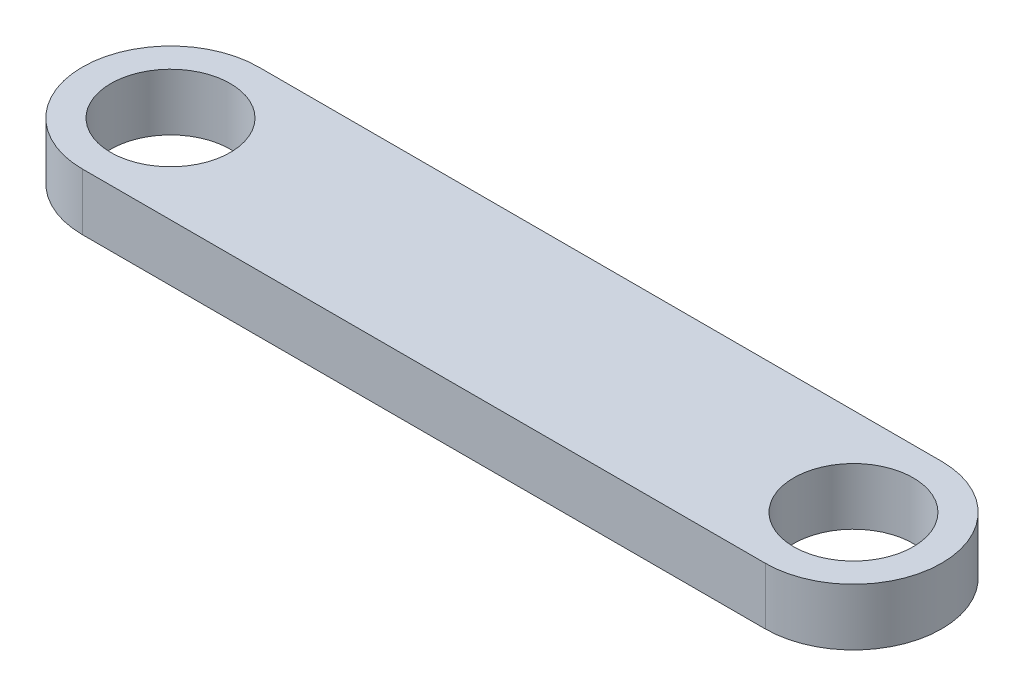
SolidWorks part; units mm, degrees
ref_plane "Front Plane" through (0, 0, 0) normal (0, 0, 1) x (1, 0, 0)
ref_plane "Top Plane" through (0, 0, 0) normal (0, 1, 0) x (1, 0, 0)
ref_plane "Right Plane" through (0, 0, 0) normal (1, 0, 0) x (0, 0, -1)
sketch "Sketch1" plane through (0, 0, 0) normal (0, 1, 0) x (1, 0, 0)
  line L0 (0, 0) -> (30.48, 0) construction
  line L1 (0, 3.937) -> (30.48, 3.937)
  line L2 (0, -3.937) -> (30.48, -3.937)
  arc A0 (0, 3.937) -> (0, -3.937) centre (0, 0) ccw
  arc A1 (30.48, -3.937) -> (30.48, 3.937) centre (30.48, 0) ccw
  circle A2 centre (0, 0) radius 2.667
  circle A3 centre (30.48, 0) radius 2.667
  point P3 (15.24, 0)
  dimension "D1" = 5.334
  dimension "D2" = 5.334
  dimension "D3" = 30.48
  dimension "D4" = 7.874
extrude "Boss-Extrude1" add sketch "Sketch1" along normal blind 2.54
equation "\"press fit\"= 0.25mm"
equation "\"shaft length\"= 1.2in"
equation "\"shaft depth\"= 2.5mm"
equation "\"shaft width\"= 8mm"
equation "\"pin diamiter\"= 5mm"
equation "\"D1@Sketch1\"=\"press fit\"+\"pin diamiter\""
equation "\"D2@Sketch1\"=\"press fit\"+\"pin diamiter\""
equation "\"D3@Sketch1\"=\"shaft length\""
equation "\"D4@Sketch1\"=\"shaft width\""
equation "\"D1@Boss-Extrude1\"=\"shaft depth\""
